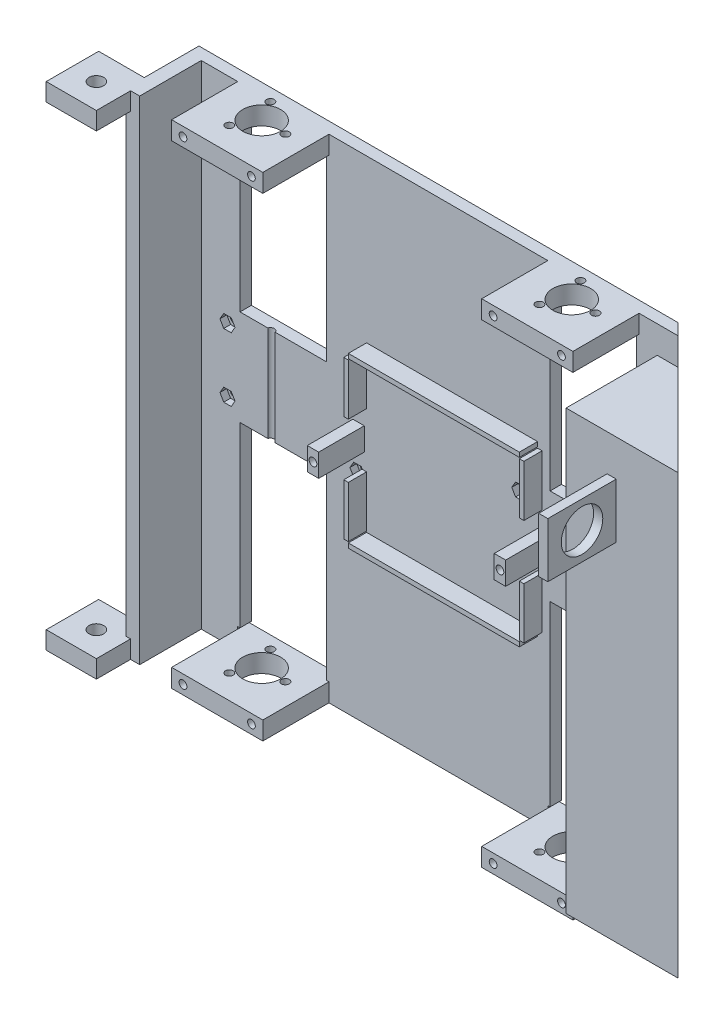
SolidWorks part; units mm, degrees
ref_plane "前视基准面" through (0, 0, 0) normal (0, 0, 1) x (1, 0, 0)
ref_plane "上视基准面" through (0, 0, 0) normal (0, 1, 0) x (1, 0, 0)
ref_plane "右视基准面" through (0, 0, 0) normal (1, 0, 0) x (0, 0, -1)
other "Configuration Table"
sketch "草图1" plane through (0, 0, 0) normal (0, 0, 1) x (1, 0, 0)
  line L1 (-110, -108) -> (110, -108)
  line L2 (-110, -108) -> (-110, 108)
  line L3 (-110, 108) -> (110, 108)
  line L4 (110, -108) -> (110, 108)
extrude "Lower_deck_5mm_Z18" add sketch "草图1" along normal blind 5 from offset 18
sketch "草图2" plane through (0, 0, 0) normal (0, 0, 1) x (1, 0, 0)
  line L1 (-87, -99) -> (-49, -99)
  line L2 (-87, -99) -> (-87, -21)
  line L3 (-87, -21) -> (-49, -21)
  line L4 (-49, -99) -> (-49, -21)
  line L5 (-87, 21) -> (-49, 21)
  line L6 (-87, 21) -> (-87, 99)
  line L7 (-87, 99) -> (-49, 99)
  line L8 (-49, 21) -> (-49, 99)
  line L9 (49, -99) -> (87, -99)
  line L10 (49, -99) -> (49, -21)
  line L11 (49, -21) -> (87, -21)
  line L12 (87, -99) -> (87, -21)
  line L13 (49, 21) -> (87, 21)
  line L14 (49, 21) -> (49, 99)
  line L15 (49, 99) -> (87, 99)
  line L16 (87, 21) -> (87, 99)
extrude "Four_recesses_for_actual_motor_bodies" cut sketch "草图2" against normal blind 30 from offset 40
sketch "草图3" plane through (0, 0, 0) normal (0, 1, 0) x (1, 0, 0)
  line L0 (110, -18) -> (-110, -18) construction
  line L1 (-88, -52) -> (-48, -52)
  line L2 (-88, -52) -> (-88, -18)
  line L3 (-88, -18) -> (-48, -18)
  line L4 (-48, -52) -> (-48, -18)
  line L6 (48, -52) -> (88, -52)
  line L7 (48, -52) -> (48, -18)
  line L8 (48, -18) -> (88, -18)
  line L9 (88, -52) -> (88, -18)
extrude "Integral_motor_seats_-1" add sketch "草图3" along normal blind 8 from offset 108
sketch "草图4" plane through (0, 0, 0) normal (0, 1, 0) x (1, 0, 0)
  line L0 (110, -18) -> (-110, -18) construction
  line L1 (-88, -52) -> (-48, -52)
  line L2 (-88, -52) -> (-88, -18)
  line L3 (-88, -18) -> (-48, -18)
  line L4 (-48, -52) -> (-48, -18)
  line L6 (48, -52) -> (88, -52)
  line L7 (48, -52) -> (48, -18)
  line L8 (48, -18) -> (88, -18)
  line L9 (88, -52) -> (88, -18)
extrude "Integral_motor_seats_1" add sketch "草图4" along normal blind 8 from offset 100
sketch "草图5" plane through (0, 0, 0) normal (0, 1, 0) x (1, 0, 0)
  circle A0 centre (-68, -32.5) radius 8.3
  circle A1 centre (-73.2, -23.4933) radius 1.7
  circle A2 centre (-73.2, -41.5067) radius 1.7
  circle A3 centre (-57.6, -32.5) radius 1.7
  circle A4 centre (68, -32.5) radius 8.3
  circle A5 centre (62.8, -23.4933) radius 1.7
  circle A6 centre (62.8, -41.5067) radius 1.7
  circle A7 centre (78.4, -32.5) radius 1.7
extrude "Coaxial_motor_pilots_and_matching_M3" cut sketch "草图5" against normal blind 110 and the other way blind 110
sketch "草图6" plane through (0, 0, 0) normal (0, 0, 1) x (1, 0, 0)
  circle A0 centre (-83, -104) radius 1.7
  circle A1 centre (-83, 104) radius 1.7
  circle A2 centre (-53, -104) radius 1.7
  circle A3 centre (-53, 104) radius 1.7
  circle A4 centre (53, -104) radius 1.7
  circle A5 centre (53, 104) radius 1.7
  circle A6 centre (83, -104) radius 1.7
  circle A7 centre (83, 104) radius 1.7
extrude "Eight_deck_connection_M3_clearance" cut sketch "草图6" against normal blind 37 from offset 54
sketch "草图7" plane through (0, 0, 0) normal (0, 0, 1) x (1, 0, 0)
  line L0 (-74.8268, -100) -> (-88, -100) construction
  line L1 (-88, -100) -> (-49, -100)
  line L2 (-88, -100) -> (-88, -99)
  line L3 (-88, -99) -> (-49, -99)
  line L4 (-49, -100) -> (-49, -99)
  line L5 (-88, 100) -> (-48, 100) construction
  line L6 (-87, 99) -> (-49, 99)
  line L7 (-87, 99) -> (-87, 100)
  line L8 (-87, 100) -> (-49, 100)
  line L9 (-49, 99) -> (-49, 100)
  line L10 (61.1732, -100) -> (48, -100) construction
  line L11 (48, -100) -> (87, -100)
  line L12 (48, -100) -> (48, -99)
  line L13 (48, -99) -> (87, -99)
  line L14 (87, -100) -> (87, -99)
  line L15 (48, 100) -> (88, 100) construction
  line L16 (49, 99) -> (87, 99)
  line L17 (49, 99) -> (49, 100)
  line L18 (49, 100) -> (87, 100)
  line L19 (87, 99) -> (87, 100)
extrude "Motor_face_clearance_to_flange_datum" cut sketch "草图7" against normal blind 5 from offset 23
sketch "草图9" plane through (0, 0, 0) normal (0, 1, 0) x (1, 0, 0)
  line L0 (100, 10) -> (170, 10)
  line L1 (170, 10) -> (170, -88)
  line L2 (170, -88) -> (100, -18)
  line L3 (100, -18) -> (100, 10)
extrude "Trim_rear_under_ramp_contact_line" cut sketch "草图9" against normal blind 110 and the other way blind 110
sketch "草图10" plane through (0, 0, 0) normal (0, 1, 0) x (1, 0, 0)
  line L0 (96, -18) -> (100, -18)
  line L1 (100, -18) -> (145, -63)
  line L2 (145, -63) -> (96, -63)
  line L3 (96, -63) -> (96, -18)
extrude "Integral45_tail_outer" add sketch "草图10" along normal blind 96 and the other way blind 96
sketch "草图11" plane through (0, 0, 0) normal (0, 1, 0) x (1, 0, 0)
  line L0 (101, -26) -> (101, -57)
  line L1 (101, -57) -> (132, -57)
  line L2 (132, -57) -> (101, -26)
extrude "Closed_tail_lightweight_core" cut sketch "草图11" against normal blind 90 and the other way blind 90
sketch "草图12" plane through (0, 0, 0) normal (0, 1, 0) x (1, 0, 0)
  line L0 (100, -18) -> (-110, -18) construction
  line L1 (-110, -50) -> (-104, -50)
  line L2 (-110, -50) -> (-110, -18)
  line L3 (-110, -18) -> (-104, -18)
  line L4 (-104, -50) -> (-104, -18)
extrude "Full_width_front_hard_stop" add sketch "草图12" along normal blind 108 and the other way blind 108
sketch "草图13" plane through (0, 0, 0) normal (0, 1, 0) x (1, 0, 0)
  line L1 (-130, -65) -> (-108, -65)
  line L2 (-130, -65) -> (-130, -42)
  line L3 (-130, -42) -> (-108, -42)
  line L4 (-108, -65) -> (-108, -42)
extrude "Direct_pivot_cheek_-108" add sketch "草图13" along normal blind 7.8 from offset 108
sketch "草图14" plane through (0, 0, 0) normal (0, 1, 0) x (1, 0, 0)
  line L1 (-130, -65) -> (-108, -65)
  line L2 (-130, -65) -> (-130, -42)
  line L3 (-130, -42) -> (-108, -42)
  line L4 (-108, -65) -> (-108, -42)
extrude "Direct_pivot_cheek_100.2" add sketch "草图14" along normal blind 7.8 from offset 100.2
sketch "草图15" plane through (0, 0, 0) normal (0, 1, 0) x (1, 0, 0)
  circle A0 centre (-119, -54) radius 3.2
extrude "M6_pivot_coaxial_bores" cut sketch "草图15" against normal blind 110 and the other way blind 110
sketch "草图16" plane through (0, 0, 0) normal (0, 1, 0) x (1, 0, 0)
  line L1 (-110.01, -38) -> (-109.2, -38)
  line L2 (-110.01, -38) -> (-110.01, -26)
  line L3 (-110.01, -26) -> (-109.2, -26)
  line L4 (-109.2, -38) -> (-109.2, -26)
extrude "Recessed_loop_patch_-65" cut sketch "草图16" against normal blind 20 from offset 45
sketch "草图17" plane through (0, 0, 0) normal (0, 1, 0) x (1, 0, 0)
  line L1 (-110.01, -38) -> (-109.2, -38)
  line L2 (-110.01, -38) -> (-110.01, -26)
  line L3 (-110.01, -26) -> (-109.2, -26)
  line L4 (-109.2, -38) -> (-109.2, -26)
extrude "Recessed_loop_patch_45" cut sketch "草图17" against normal blind 20 from offset 65
sketch "草图18" plane through (0, 0, 0) normal (0, 0, 1) x (1, 0, 0)
  line L1 (-37.5, -5) -> (-32.5, -5)
  line L2 (-37.5, -5) -> (-37.5, 5)
  line L3 (-37.5, 5) -> (-32.5, 5)
  line L4 (-32.5, -5) -> (-32.5, 5)
  line L6 (44.5, -5) -> (49.5, -5)
  line L7 (44.5, -5) -> (44.5, 5)
  line L8 (44.5, 5) -> (49.5, 5)
  line L9 (49.5, -5) -> (49.5, 5)
extrude "Battery_integral_clamp_posts" add sketch "草图18" along normal blind 20 from offset 23
sketch "草图19" plane through (0, 0, 0) normal (0, 0, 1) x (1, 0, 0)
  line L1 (-31.5, -37) -> (43.5, -37)
  line L2 (-31.5, -37) -> (-31.5, -35)
  line L3 (-31.5, -35) -> (43.5, -35)
  line L4 (43.5, -37) -> (43.5, -35)
  line L6 (-31.5, 35) -> (43.5, 35)
  line L7 (-31.5, 35) -> (-31.5, 37)
  line L8 (-31.5, 37) -> (43.5, 37)
  line L9 (43.5, 35) -> (43.5, 37)
  line L11 (-33.5, -34.5) -> (-31.5, -34.5)
  line L12 (-33.5, -34.5) -> (-33.5, -12)
  line L13 (-33.5, -12) -> (-31.5, -12)
  line L14 (-31.5, -34.5) -> (-31.5, -12)
  line L16 (43.5, -34.5) -> (45.5, -34.5)
  line L17 (43.5, -34.5) -> (43.5, -12)
  line L18 (43.5, -12) -> (45.5, -12)
  line L19 (45.5, -34.5) -> (45.5, -12)
  line L21 (-33.5, 12) -> (-31.5, 12)
  line L22 (-33.5, 12) -> (-33.5, 34.5)
  line L23 (-33.5, 34.5) -> (-31.5, 34.5)
  line L24 (-31.5, 12) -> (-31.5, 34.5)
  line L26 (43.5, 12) -> (45.5, 12)
  line L27 (43.5, 12) -> (43.5, 34.5)
  line L28 (43.5, 34.5) -> (45.5, 34.5)
  line L29 (45.5, 12) -> (45.5, 34.5)
extrude "Battery_short_lateral_locators" add sketch "草图19" along normal blind 8 from offset 23
sketch "草图20" plane through (0, 0, 0) normal (0, 0, 1) x (1, 0, 0)
  circle A0 centre (-35, 0) radius 1.7
  circle A1 centre (47, 0) radius 1.7
extrude "Battery_M3_through_columns" cut sketch "草图20" against normal blind 27 from offset 44
sketch "草图21" plane through (0, 0, 0) normal (0, 0, 1) x (1, 0, 0)
  circle A0 centre (-92.5, -11.5) radius 1.7
  circle A1 centre (-35.5, -11.5) radius 1.7
  circle A2 centre (-92.5, 11.5) radius 1.7
  circle A3 centre (-35.5, 11.5) radius 1.7
  circle A4 centre (35.5, -11.5) radius 1.7
  circle A5 centre (92.5, -11.5) radius 1.7
  circle A6 centre (35.5, 11.5) radius 1.7
  circle A7 centre (92.5, 11.5) radius 1.7
sketch "草图22" plane through (0, 0, 0) normal (0, 0, 1) x (1, 0, 0)
  circle A0 centre (-92.5, -14) radius 1.7
  circle A1 centre (-92.5, 14) radius 1.7
  circle A2 centre (-35.5, -14) radius 1.7
  circle A3 centre (-35.5, 14) radius 1.7
  circle A4 centre (35.5, -14) radius 1.7
  circle A5 centre (35.5, 14) radius 1.7
  circle A6 centre (92.5, -14) radius 1.7
  circle A7 centre (92.5, 14) radius 1.7
extrude "Four_gray_mounting_pairs" cut sketch "草图22" against normal blind 7 from offset 24
sketch "草图23" plane through (0, 0, 0) normal (0, 0, 1) x (1, 0, 0)
  line L0 (-89.2, -14) -> (-90.85, -11.1421)
  line L1 (-90.85, -11.1421) -> (-94.15, -11.1421)
  line L2 (-94.15, -11.1421) -> (-95.8, -14)
  line L3 (-95.8, -14) -> (-94.15, -16.8579)
  line L4 (-94.15, -16.8579) -> (-90.85, -16.8579)
  line L5 (-90.85, -16.8579) -> (-89.2, -14)
  line L6 (-89.2, 14) -> (-90.85, 16.8579)
  line L7 (-90.85, 16.8579) -> (-94.15, 16.8579)
  line L8 (-94.15, 16.8579) -> (-95.8, 14)
  line L9 (-95.8, 14) -> (-94.15, 11.1421)
  line L10 (-94.15, 11.1421) -> (-90.85, 11.1421)
  line L11 (-90.85, 11.1421) -> (-89.2, 14)
  line L12 (-32.2, -14) -> (-33.85, -11.1421)
  line L13 (-33.85, -11.1421) -> (-37.15, -11.1421)
  line L14 (-37.15, -11.1421) -> (-38.8, -14)
  line L15 (-38.8, -14) -> (-37.15, -16.8579)
  line L16 (-37.15, -16.8579) -> (-33.85, -16.8579)
  line L17 (-33.85, -16.8579) -> (-32.2, -14)
  line L18 (-32.2, 14) -> (-33.85, 16.8579)
  line L19 (-33.85, 16.8579) -> (-37.15, 16.8579)
  line L20 (-37.15, 16.8579) -> (-38.8, 14)
  line L21 (-38.8, 14) -> (-37.15, 11.1421)
  line L22 (-37.15, 11.1421) -> (-33.85, 11.1421)
  line L23 (-33.85, 11.1421) -> (-32.2, 14)
  line L24 (38.8, -14) -> (37.15, -11.1421)
  line L25 (37.15, -11.1421) -> (33.85, -11.1421)
  line L26 (33.85, -11.1421) -> (32.2, -14)
  line L27 (32.2, -14) -> (33.85, -16.8579)
  line L28 (33.85, -16.8579) -> (37.15, -16.8579)
  line L29 (37.15, -16.8579) -> (38.8, -14)
  line L30 (38.8, 14) -> (37.15, 16.8579)
  line L31 (37.15, 16.8579) -> (33.85, 16.8579)
  line L32 (33.85, 16.8579) -> (32.2, 14)
  line L33 (32.2, 14) -> (33.85, 11.1421)
  line L34 (33.85, 11.1421) -> (37.15, 11.1421)
  line L35 (37.15, 11.1421) -> (38.8, 14)
  line L36 (95.8, -14) -> (94.15, -11.1421)
  line L37 (94.15, -11.1421) -> (90.85, -11.1421)
  line L38 (90.85, -11.1421) -> (89.2, -14)
  line L39 (89.2, -14) -> (90.85, -16.8579)
  line L40 (90.85, -16.8579) -> (94.15, -16.8579)
  line L41 (94.15, -16.8579) -> (95.8, -14)
  line L42 (95.8, 14) -> (94.15, 16.8579)
  line L43 (94.15, 16.8579) -> (90.85, 16.8579)
  line L44 (90.85, 16.8579) -> (89.2, 14)
  line L45 (89.2, 14) -> (90.85, 11.1421)
  line L46 (90.85, 11.1421) -> (94.15, 11.1421)
  line L47 (94.15, 11.1421) -> (95.8, 14)
extrude "Gray_captive_nuts_top_loading" cut sketch "草图23" against normal blind 3 from offset 23
sketch "草图24" plane through (0, 0, 0) normal (0, 0, 1) x (1, 0, 0)
  line L1 (114, 56) -> (118, 56)
  line L2 (114, 56) -> (114, 80)
  line L3 (114, 80) -> (118, 80)
  line L4 (118, 56) -> (118, 80)
extrude "Rear_photoeye_on_tail_top_not_contact_ramp" add sketch "草图24" along normal blind 30 from offset 63
sketch "草图25" plane through (0, 0, 0) normal (1, 0, 0) x (0, 0, -1)
  circle A0 centre (-78, 68) radius 9.1
extrude "Rear_M18_clearance" cut sketch "草图25" against normal blind 4 from offset 118
